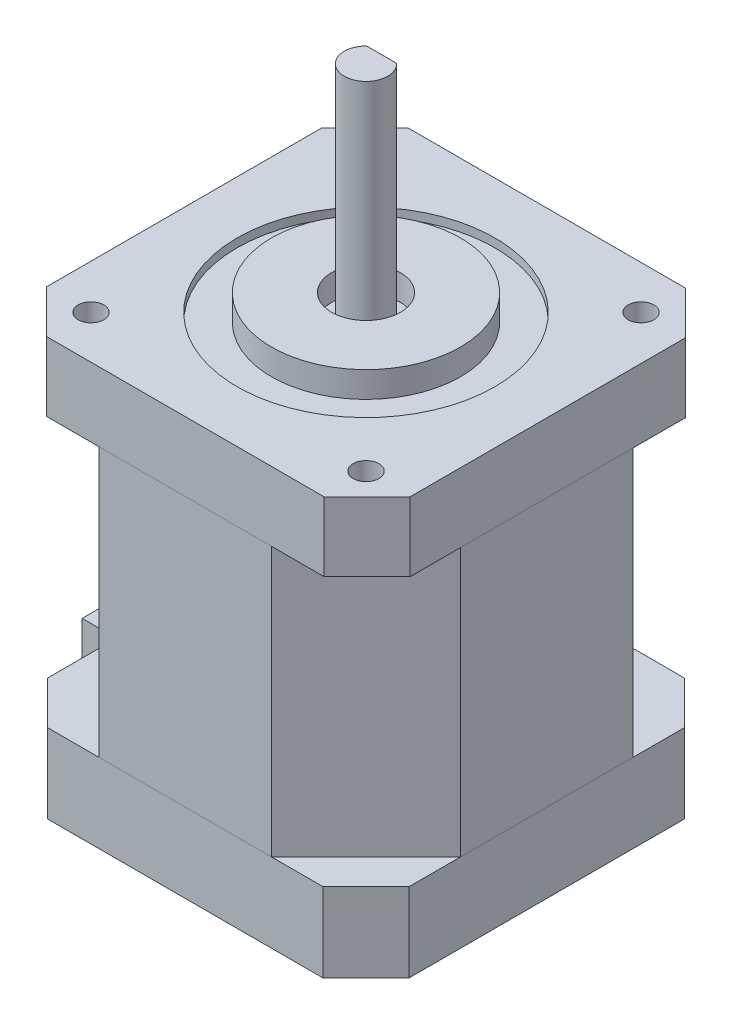
SolidWorks part; units mm, degrees
ref_plane "Front Plane" through (0, 0, 0) normal (0, 0, 1) x (1, 0, 0)
ref_plane "Top Plane" through (0, 0, 0) normal (0, 1, 0) x (1, 0, 0)
ref_plane "Right Plane" through (0, 0, 0) normal (1, 0, 0) x (0, 0, -1)
sketch "Sketch2" plane through (0, 0, 0) normal (0, 0, 1) x (1, 0, 0)
  line L1 (-21.025, -21.025) -> (21.025, -21.025)
  line L2 (-21.025, -21.025) -> (-21.025, 21.025)
  line L3 (-21.025, 21.025) -> (21.025, 21.025)
  line L4 (21.025, -21.025) -> (21.025, 21.025)
  line L5 (-21.025, -21.025) -> (21.025, 21.025) construction
  line L6 (-21.025, 21.025) -> (21.025, -21.025) construction
  point P0 (0, 0)
  dimension "D1" = 42.05
  dimension "D2" = 42.05
extrude "Boss-Extrude1" add sketch "Sketch2" along normal blind 9.2
chamfer "Chamfer1" distance 5 angle 45 4 edges at (21.025, -21.025, 4.6) (21.025, 21.025, 4.6) (-21.025, 21.025, 4.6) (-21.025, -21.025, 4.6)
sketch "Sketch3" plane through (0, 0, 9.2) normal (0, 0, 1) x (1, 0, 0)
  line L0 (-21.025, 11.025) -> (-11.025, 21.025)
  line L1 (-10.025, -21.025) -> (10.025, -21.025)
  line L2 (-21.025, -10.025) -> (-21.025, 11.025)
  line L3 (-11.025, 21.025) -> (10.025, 21.025)
  line L4 (21.025, -10.025) -> (21.025, 10.025)
  line L5 (-21.025, -21.025) -> (21.025, 21.025) construction
  line L6 (-21.025, 21.025) -> (21.025, -21.025) construction
  line L7 (10.025, 21.025) -> (21.025, 10.025)
  line L8 (10.025, -21.025) -> (21.025, -10.025)
  line L9 (-21.025, -10.025) -> (-10.025, -21.025)
  point P0 (0, 0)
extrude "Boss-Extrude2" add sketch "Sketch3" along normal blind 31.3 separate body
sketch "Sketch4" plane through (0, 0, 40.5) normal (0, 0, 1) x (1, 0, 0)
  line L1 (-21.1528, -21.025) -> (21.1528, -21.025)
  line L2 (-21.1528, -21.025) -> (-21.1528, 21.025)
  line L3 (-21.1528, 21.025) -> (21.1528, 21.025)
  line L4 (21.1528, -21.025) -> (21.1528, 21.025)
  line L5 (-21.1528, -21.025) -> (21.1528, 21.025) construction
  line L6 (-21.1528, 21.025) -> (21.1528, -21.025) construction
  point P0 (0, 0)
extrude "Boss-Extrude3" add sketch "Sketch4" along normal blind 8.05 separate body
chamfer "Chamfer2" distance 5 angle 45 4 edges at (21.1528, -21.025, 44.525) (21.1528, 21.025, 44.525) (-21.1528, 21.025, 44.525) (-21.1528, -21.025, 44.525)
sketch "Sketch5" plane through (0, 0, 48.55) normal (0, 0, 1) x (1, 0, 0)
  circle A0 centre (0, 0) radius 15
extrude "Cut-Extrude1" cut sketch "Sketch5" against normal blind 1
sketch "Sketch6" plane through (0, 0, 47.55) normal (0, 0, 1) x (1, 0, 0)
  circle A0 centre (0, 0) radius 11
extrude "Boss-Extrude5" add sketch "Sketch6" along normal blind 3
sketch "Sketch7" plane through (0, 0, 50.55) normal (0, 0, 1) x (1, 0, 0)
  circle A0 centre (0, 0) radius 4
extrude "Cut-Extrude2" cut sketch "Sketch7" against normal blind 3
sketch "Sketch8" plane through (0, 0, 47.55) normal (0, 0, 1) x (1, 0, 0)
  circle A0 centre (0, 0) radius 2.525
extrude "Boss-Extrude6" add sketch "Sketch8" along normal blind 26.05
sketch "Sketch9" plane through (0, 0, 73.6) normal (0, 0, 1) x (1, 0, 0)
  line L0 (-1.745, 1.825) -> (1.745, 1.825)
  arc A0 (-1.745, 1.825) -> (1.745, 1.825) centre (0, 0) ccw
  circle A1 centre (0, 0) radius 3
  dimension "D2" = 6
  dimension "D1" = 1.825
extrude "Cut-Extrude3" cut sketch "Sketch9" against normal blind 24.05
sketch "Sketch10" plane through (-21.025, 0, 0) normal (-1, 0, 0) x (0, 0, 1)
  line L0 (0, 8) -> (0, -8)
  line L1 (0, 8) -> (2, 8)
  line L2 (0, -8) -> (2, -8)
  line L3 (2, 8) -> (2, -8)
  line L4 (0, 16.025) -> (0, -16.025) construction
  point P6 (0, 0)
  dimension "D1" = 16
  dimension "D2" = 2
extrude "Boss-Extrude7" add sketch "Sketch10" along normal blind 4
sketch "Sketch11" plane through (-21.025, 0, 0) normal (-1, 0, 0) x (0, 0, 1)
  line L0 (9.2, 11.025) -> (9.2, -10.025) construction
  line L1 (3.2, 8) -> (9.2, 8)
  line L2 (3.2, 8) -> (3.2, -8)
  line L3 (3.2, -8) -> (9.2, -8)
  line L4 (9.2, 8) -> (9.2, -8)
  line L5 (3.2, 8) -> (9.2, -8) construction
  line L6 (3.2, -8) -> (9.2, 8) construction
  line L8 (2, 8) -> (0, 8) construction
  point P0 (6.2, 0)
  dimension "D1" = 6
  dimension "D2" = 16
extrude "Boss-Extrude8" add sketch "Sketch11" along normal blind 4 separate body
sketch "Sketch12" plane through (-25.025, 0, 0) normal (-1, 0, 0) x (0, 0, 1)
  line L0 (8.2, 4) -> (10.0297, 4)
  line L1 (4.2, -6.5) -> (8.2, -6.5)
  line L2 (4.2, -6.5) -> (4.2, 6.5)
  line L3 (4.2, 6.5) -> (8.2, 6.5)
  line L4 (8.2, -6.5) -> (8.2, -4)
  line L7 (3.2, -8) -> (9.2, -8) construction
  line L8 (3.2, 8) -> (3.2, -8) construction
  line L13 (10.0297, 4) -> (10.0297, -4)
  line L20 (8.2, -4) -> (10.0297, -4)
  line L21 (8.2, 4) -> (8.2, 6.5)
  point P0 (6.2, 0)
  point P9 (8.6892, 0)
  dimension "D1" = 13
  dimension "D2" = 4
  dimension "D3" = 1.5
  dimension "D4" = 1
extrude "Cut-Extrude4" cut sketch "Sketch12" against normal blind 4
move or copy body "Body-Move/Copy1" bodies to move or copy 110 109 112 102 copy no rotation origin (0, 0, 36.8) rotation axis (-1, 0, 0) rotation angle 90
sketch "Sketch13" plane through (0, -36.8, 0) normal (0, -1, 0) x (1, 0, 0)
  circle A0 centre (0, 36.8) radius 4.65
  dimension "D1" = 9.3
extrude "Cut-Extrude5" cut sketch "Sketch13" against normal blind 4.1
sketch "Sketch14" plane through (0, -36.8, 0) normal (0, -1, 0) x (-1, 0, 0)
  line L1 (15.5, -21.3) -> (-15.5, -21.3)
  line L2 (15.5, -21.3) -> (15.5, -52.3)
  line L3 (15.5, -52.3) -> (-15.5, -52.3)
  line L4 (-15.5, -21.3) -> (-15.5, -52.3)
  line L5 (15.5, -21.3) -> (-15.5, -52.3) construction
  line L6 (15.5, -52.3) -> (-15.5, -21.3) construction
  circle A0 centre (15.5, -52.3) radius 3
  circle A1 centre (-15.5, -52.3) radius 3
  circle A2 centre (-15.5, -21.3) radius 3
  circle A3 centre (15.5, -21.3) radius 3
  point P0 (0, -36.8)
  dimension "D3" = 6
  dimension "D1" = 31
  dimension "D2" = 31
extrude "Cut-Extrude6" cut sketch "Sketch14" against normal blind 2 contours L3 A0 L2 | L2 A0 L3 | L4 A1 L3 | L3 A1 L4 | L1 A2 L4 | L4 A2 L1 | L1 A3 L2 | L2 A3 L1
sketch "Sketch15" plane through (0, 11.75, 0) normal (0, 1, 0) x (1, 0, 0)
  line L1 (-17.5, -54.3) -> (17.5, -54.3)
  line L2 (-17.5, -54.3) -> (-17.5, -19.3)
  line L3 (-17.5, -19.3) -> (17.5, -19.3)
  line L4 (17.5, -54.3) -> (17.5, -19.3)
  line L5 (-17.5, -54.3) -> (17.5, -19.3) construction
  line L6 (-17.5, -19.3) -> (17.5, -54.3) construction
  circle A0 centre (-16, -20.8) radius 1.5
  circle A1 centre (16, -20.8) radius 1.5
  circle A2 centre (16, -52.8) radius 1.5
  circle A3 centre (-16, -52.8) radius 1.5
  point P0 (0, -36.8)
  dimension "D3" = 3
  dimension "D1" = 35
  dimension "D2" = 35
extrude "Cut-Extrude7" cut sketch "Sketch15" against normal blind 5 contours A1 | A2 | A3 L2 | A0
